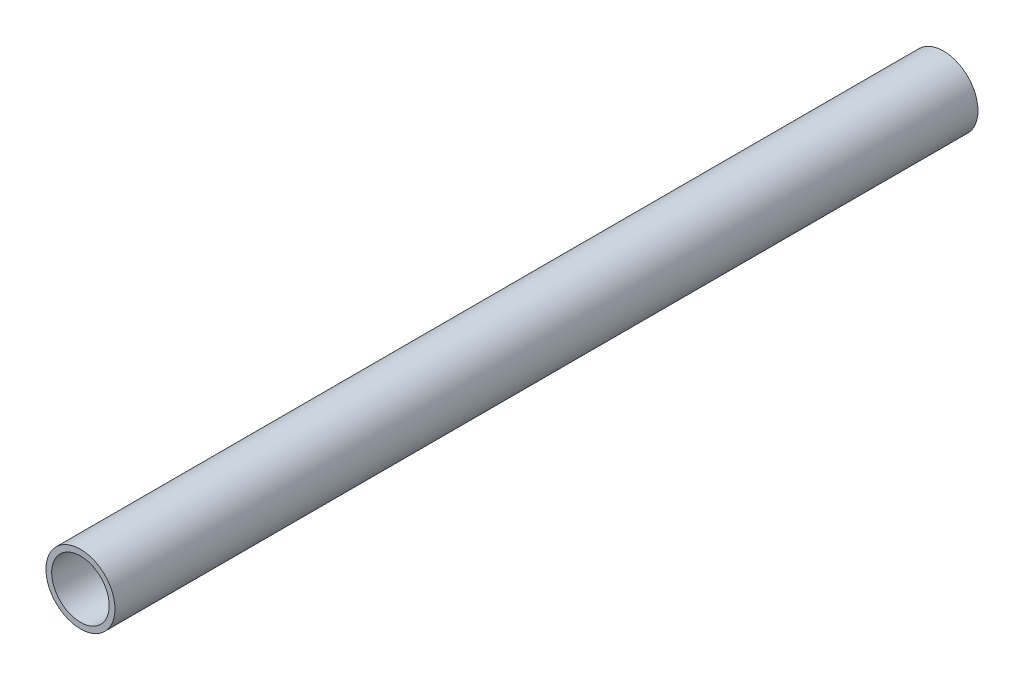
SolidWorks part; units mm, degrees
ref_plane "Front Plane" through (0, 0, 0) normal (0, 0, 1) x (1, 0, 0)
ref_plane "Top Plane" through (0, 0, 0) normal (0, 1, 0) x (1, 0, 0)
ref_plane "Right Plane" through (0, 0, 0) normal (1, 0, 0) x (0, 0, -1)
sketch "Sketch1" plane through (0, 0, 0) normal (0, 0, 1) x (1, 0, 0)
  circle A0 centre (0, 0) radius 6
  circle A1 centre (0, 0) radius 5
  dimension "D2" = 12
  dimension "D1" = 1
extrude "Boss-Extrude1" add sketch "Sketch1" along normal blind 150
sketch "Sketch2" plane through (0, 0, 0) normal (0, 1, 0) x (1, 0, 0)
  line L0 (-6, -75) -> (6, -75) construction
  line L1 (-6, 0) -> (-6, -150) construction
  line L2 (6, -150) -> (6, 0) construction
ref_plane "Plane1" through (0, 0, 75) normal (0, 0, 1) x (1, 0, 0)
